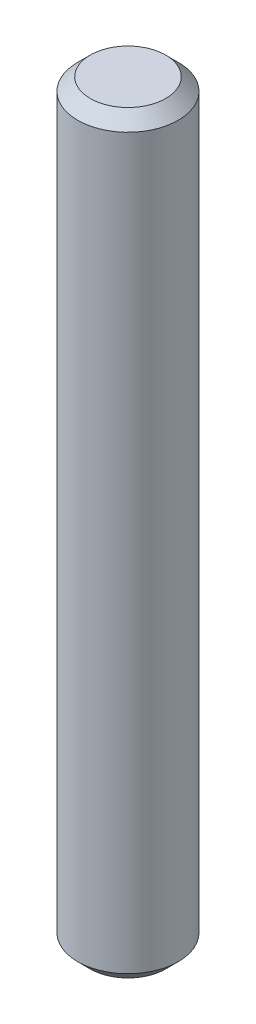
SolidWorks part; units mm, degrees
ref_plane "Front Plane" through (0, 0, 0) normal (0, 0, 1) x (1, 0, 0)
ref_plane "Top Plane" through (0, 0, 0) normal (0, 1, 0) x (1, 0, 0)
ref_plane "Right Plane" through (0, 0, 0) normal (1, 0, 0) x (0, 0, -1)
sketch "Sketch1" plane through (0, 0, 0) normal (0, 1, 0) x (1, 0, 0)
  circle A0 centre (0, 0) radius 2
  dimension "D1" = 4
extrude "Boss-Extrude1" add sketch "Sketch1" along normal blind 30
chamfer "Chamfer1" distance 0.5 angle 45 2 edges at (0, 0, 2) (0, 30, 2)
